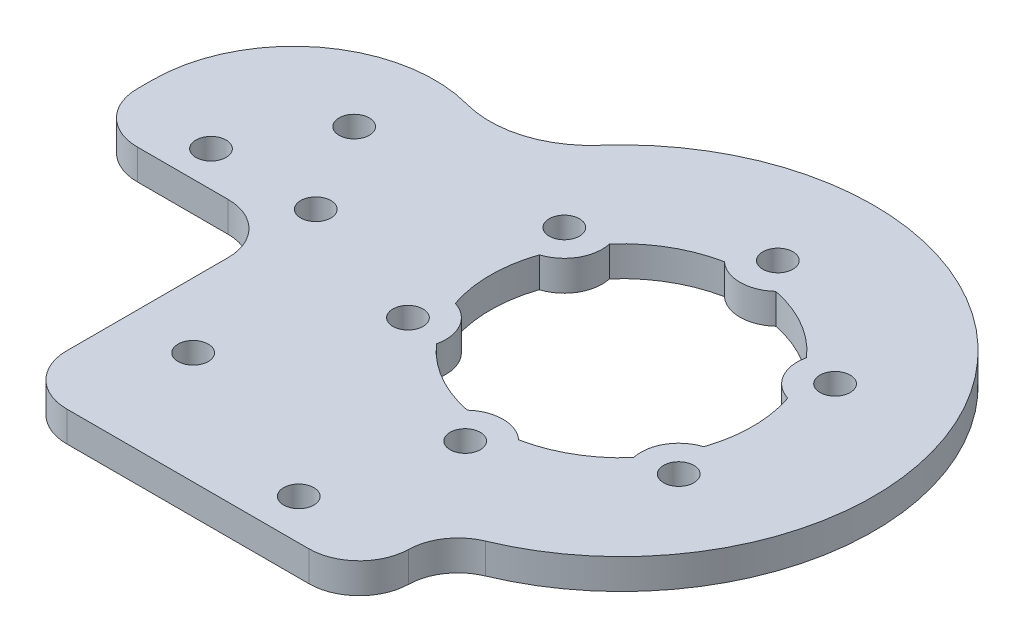
SolidWorks part; units mm, degrees
ref_plane "前视基准面" through (0, 0, 0) normal (0, 0, 1) x (1, 0, 0)
ref_plane "上视基准面" through (0, 0, 0) normal (0, 1, 0) x (1, 0, 0)
ref_plane "右视基准面" through (0, 0, 0) normal (1, 0, 0) x (0, 0, -1)
sketch "草图1" plane through (0, 0, 0) normal (0, 1, 0) x (1, 0, 0)
  line L0 (-46.5, -0.005) -> (-18.5, -0.005) construction
  line L1 (-46.5, -0.005) -> (-46.5, -6.505)
  line L2 (6.5, -24.1402) -> (6.5, -32.5)
  line L3 (0, 0) -> (0, 15.5) construction
  line L4 (-27.3038, -3.005) -> (-3.5, -28.5) construction
  line L5 (-15.4019, -15.7525) -> (-21.0588, -21.4094) construction
  line L6 (6.5, -32.5) -> (6.5, -18.5) construction
  line L7 (6.5, -18.5) -> (0, -18.5) construction
  line L8 (-27.5, -6.505) -> (-27.5, -32.5)
  line L9 (-27.5, -6.505) -> (-46.5, -6.505)
  line L10 (0, 0) -> (-9.7664, 8.58) construction
  line L11 (-27.5, -32.5) -> (6.5, -32.5)
  arc A0 (6.5, -24.1402) -> (-22.8516, 10.1393) centre (0, 0) ccw
  arc A1 (-18.5, -0.005) -> (0, -18.5) centre (0, 0) ccw construction
  arc A2 (-22.8516, 10.1393) -> (-46.5, -0.005) centre (-32.5, -0.005) ccw
  circle A3 centre (-32.5, -0.005) radius 6 construction
  circle A4 centre (-32.5, 5.995) radius 1.5
  circle A5 centre (-27.3038, -3.005) radius 1.5
  circle A6 centre (-3.5, -28.5) radius 1.5
  circle A7 centre (-37.6962, -3.005) radius 1.5
  circle A8 centre (0, 0) radius 15.5 construction
  circle A9 centre (-21.0588, -21.4094) radius 1.5
  circle A10 centre (0, 15.5) radius 1.5
  circle A11 centre (13.4234, 7.75) radius 1.5
  circle A12 centre (13.4234, -7.75) radius 1.5
  circle A13 centre (0, -15.5) radius 1.5
  circle A14 centre (-13.4234, -7.75) radius 1.5
  circle A15 centre (-13.4234, 7.75) radius 1.5
  arc A16 (-12.3137, 4.1679) -> (-12.3137, -4.1679) centre (0, 0) ccw
  arc A17 (-2.5473, 12.748) -> (2.5473, 12.748) centre (0, 15.5) ccw
  arc A18 (9.7664, 8.58) -> (12.3137, 4.1679) centre (13.4234, 7.75) ccw
  arc A19 (12.3137, -4.1679) -> (9.7664, -8.58) centre (13.4234, -7.75) ccw
  arc A20 (2.5473, -12.748) -> (-2.5473, -12.748) centre (0, -15.5) ccw
  arc A21 (-9.7664, -8.58) -> (-12.3137, -4.1679) centre (-13.4234, -7.75) ccw
  arc A22 (-12.3137, 4.1679) -> (-9.7664, 8.58) centre (-13.4234, 7.75) ccw
  arc A23 (-2.5473, 12.748) -> (-9.7664, 8.58) centre (0, 0) ccw
  arc A24 (9.7664, 8.58) -> (2.5473, 12.748) centre (0, 0) ccw
  arc A25 (12.3137, -4.1679) -> (12.3137, 4.1679) centre (0, 0) ccw
  arc A26 (2.5473, -12.748) -> (9.7664, -8.58) centre (0, 0) ccw
  arc A27 (-9.7664, -8.58) -> (-2.5473, -12.748) centre (0, 0) ccw
  point P26 (-32.5, -0.005)
  dimension "D3" = 32.5
  dimension "D1" = 14
  dimension "D2" = 18.5
  dimension "D6" = 12
  dimension "D8" = 3
  dimension "D9" = 6.5
  dimension "D12" = 6.5
  dimension "D13" = 3
  dimension "D15" = 50
  dimension "D16" = 31
  dimension "D17" = 3
  dimension "D20" = 13
  dimension "D21" = 6
  dimension "D22" = 3.75
  dimension "D4" = 19
  dimension "D5" = 25.995
  dimension "D10" = 10
  dimension "D11" = 10
  dimension "D14" = 8
  dimension "D19" = 15.5
  dimension "D7" = 3
  dimension "D18" = 6
extrude "凸台-拉伸1" add sketch "草图1" along normal blind 3
fillet "圆角1" radius 5 3 edges at (-46.5, 1.5, 6.505) (-27.5, 1.5, 32.5) (-27.5, 1.5, 6.505)
fillet "圆角2" radius 10 1 edges at (-22.8516, 1.5, -10.1393)
fillet "圆角6" radius 5 1 edges at (6.5, 1.5, 24.1402)
fillet "圆角7" radius 5 1 edges at (6.5, 1.5, 32.5)
